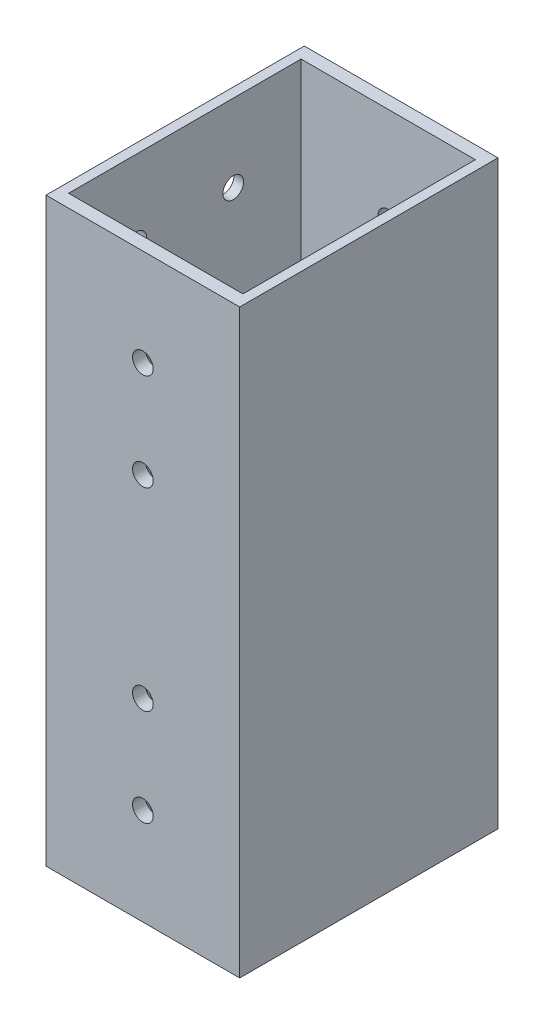
SolidWorks part; units mm, degrees
ref_plane "前视基准面" through (0, 0, 0) normal (0, 0, 1) x (1, 0, 0)
ref_plane "上视基准面" through (0, 0, 0) normal (0, 1, 0) x (1, 0, 0)
ref_plane "右视基准面" through (0, 0, 0) normal (1, 0, 0) x (0, 0, -1)
sketch "草图1" plane through (0, 0, 0) normal (0, 1, 0) x (1, 0, 0)
  line L1 (-15, -20) -> (15, -20)
  line L2 (-15, -20) -> (-15, 20)
  line L3 (-15, 20) -> (15, 20)
  line L4 (15, -20) -> (15, 20)
  line L5 (-15, -20) -> (15, 20) construction
  line L6 (-15, 20) -> (15, -20) construction
  line L7 (-13.5, -18) -> (13.5, -18)
  line L8 (-13.5, -18) -> (-13.5, 18)
  line L9 (-13.5, 18) -> (13.5, 18)
  line L10 (13.5, -18) -> (13.5, 18)
  line L11 (-13.5, -18) -> (13.5, 18) construction
  line L12 (-13.5, 18) -> (13.5, -18) construction
  point P0 (0, 0)
  point P6 (0, 0)
  dimension "D1" = 40
  dimension "D2" = 30
  dimension "D3" = 36
extrude "凸台-拉伸1" add sketch "草图1" along normal blind 90
sketch "草图2" plane through (-15, 0, 0) normal (-1, 0, 0) x (0, 0, 1)
  circle A0 centre (7.5, 78) radius 1.6
  circle A1 centre (-7.5, 78) radius 1.6
  circle A2 centre (-7.5, 62) radius 1.6
  circle A3 centre (7.5, 62) radius 1.6
  circle A5 centre (7.5, 28) radius 1.6
  circle A6 centre (7.5, 12) radius 1.6
  circle A7 centre (-7.5, 28) radius 1.6
  circle A8 centre (-7.5, 12) radius 1.6
  dimension "D1" = 3.2
  dimension "D2" = 3.2
  dimension "D3" = 3.2
  dimension "D4" = 3.2
  dimension "D5" = 3.2
  dimension "D6" = 3.2
  dimension "D7" = 3.2
  dimension "D8" = 3.2
extrude "切除-拉伸1" cut sketch "草图2" against normal up to next
sketch "草图3" plane through (0, 0, 18) normal (0, 0, -1) x (-1, 0, 0)
  line L0 (-15, 90) -> (15, 90) construction
  line L1 (-15, 90) -> (-15, 0) construction
  line L2 (-15, 0) -> (15, 0) construction
  circle A0 centre (0, 30) radius 1.6
  circle A1 centre (0, 15) radius 1.6
  circle A2 centre (0, 75) radius 1.6
  circle A3 centre (0, 60) radius 1.6
  dimension "D1" = 3.2
  dimension "D2" = 3.2
  dimension "D3" = 3.2
  dimension "D4" = 3.2
  dimension "D5" = 15
  dimension "D6" = 30
  dimension "D7" = 15
  dimension "D8" = 15
  dimension "D9" = 15
  dimension "D10" = 30
  dimension "D11" = 15
  dimension "D12" = 15
extrude "切除-拉伸2" cut sketch "草图3" against normal through all both and the other way through all
